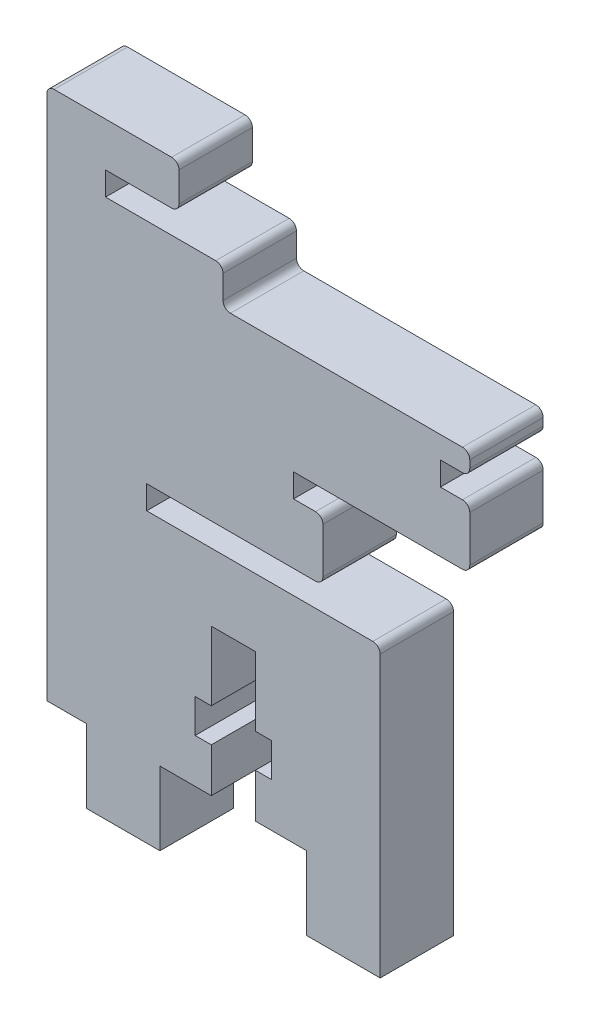
SolidWorks part; units mm, degrees
ref_plane "Front Plane" through (0, 0, 0) normal (0, 0, 1) x (1, 0, 0)
ref_plane "Top Plane" through (0, 0, 0) normal (0, 1, 0) x (1, 0, 0)
ref_plane "Right Plane" through (0, 0, 0) normal (1, 0, 0) x (0, 0, -1)
sketch "Sketch1" plane through (0, 0, 0) normal (0, 0, 1) x (1, 0, 0)
  line L1 (20, 5) -> (20, 19.6) construction
  line L3 (4.1, 19.6) -> (4.1, 21.2)
  line L4 (4.1, 21.2) -> (16.1, 21.2)
  line L5 (16.1, 21.2) -> (16.1, 25.3)
  line L8 (10, 5) -> (10, 15.0197) construction
  line L9 (8.5, 5) -> (5, 5)
  line L10 (5, 0) -> (0, 0)
  line L11 (0, 0) -> (0, 5)
  line L12 (5, 0) -> (5, 5)
  line L13 (11.5, 5) -> (15, 5)
  line L14 (15, 5) -> (15, 0)
  line L15 (15, 0) -> (20, 0)
  line L16 (20, 0) -> (20, 5)
  line L17 (8.5, 5) -> (11.5, 5) construction
  line L18 (11.5, 5) -> (11.5, 8)
  line L19 (11.5, 10.3) -> (12.6, 10.3)
  line L20 (7.4, 8) -> (7.4, 10.3)
  line L21 (12.6, 8) -> (11.5, 8)
  line L22 (11.5, 10.3) -> (11.5, 15)
  line L23 (11.5, 15) -> (8.5, 15)
  line L24 (8.5, 15) -> (8.5, 10.3)
  line L25 (8.5, 8) -> (7.4, 8)
  line L26 (12.6, 10.3) -> (12.6, 8)
  line L27 (7.4, 10.3) -> (8.5, 10.3)
  line L28 (8.5, 8) -> (8.5, 5)
  line L29 (10, 15) -> (10, 5) construction
  line L30 (16.1, 25.3) -> (14.1, 25.3)
  line L31 (14.1, 25.3) -> (14.1, 26.9)
  line L32 (14.1, 26.9) -> (26.1, 26.9)
  line L33 (26.1, 26.9) -> (26.1, 31)
  line L37 (20, 19.6) -> (20, 5)
  line L39 (26.1, 31) -> (24.1, 31)
  line L40 (24.1, 31) -> (24.1, 32.6)
  line L41 (24.1, 32.6) -> (26.1, 32.6)
  line L47 (6.3, 41.3) -> (-2.7, 41.3)
  line L49 (26.1, 32.6) -> (26.1, 36.7) construction
  line L50 (26.1, 36.7) -> (1.3, 36.7) construction
  line L51 (1.3, 36.7) -> (1.3, 38.3)
  line L52 (1.3, 38.3) -> (6.3, 38.3)
  line L53 (6.3, 38.3) -> (6.3, 41.3)
  line L54 (4.1, 19.6) -> (20, 19.6)
  line L55 (26.1, 32.6) -> (26.1, 34.1)
  line L56 (26.1, 34.1) -> (9.3, 34.1)
  line L57 (9.3, 34.1) -> (9.3, 36.7)
  line L58 (9.3, 36.7) -> (1.3, 36.7)
  line L59 (0, 5) -> (-2.7, 5)
  line L60 (-2.7, 5) -> (-2.7, 41.3)
  dimension "D3" = 12
  dimension "D4" = 5.7
  dimension "D5" = 10
  dimension "D6" = 5
  dimension "D7" = 5
  dimension "D8" = 5.2
  dimension "D9" = 3
  dimension "D10" = 2.3
  dimension "D11" = 3
  dimension "D12" = 10
  dimension "D13" = 4
  dimension "D14" = 10
  dimension "D15" = 5
  dimension "D16" = 1.6
  dimension "D18" = 5.7
  dimension "D19" = 3
  dimension "D20" = 22.8
  dimension "D21" = 2.6
  dimension "D22" = 8
  dimension "D23" = 2.7
  dimension "D24" = 5.7
  dimension "D25" = 14.6
  dimension "D26" = 10
extrude "Boss-Extrude1" add sketch "Sketch1" along normal blind 5
fillet "Fillet3" radius 0.5 12 edges at (16.1, 21.2, 2.5) (20, 19.6, 2.5) (6.3, 38.3, 2.5) (6.3, 41.3, 2.5) (26.1, 26.9, 2.5) (26.1, 31, 2.5) (16.1, 25.3, 2.5) (26.1, 32.6, 2.5) (26.1, 34.1, 2.5) (9.3, 34.1, 2.5) (9.3, 36.7, 2.5) (-2.7, 41.3, 2.5)
